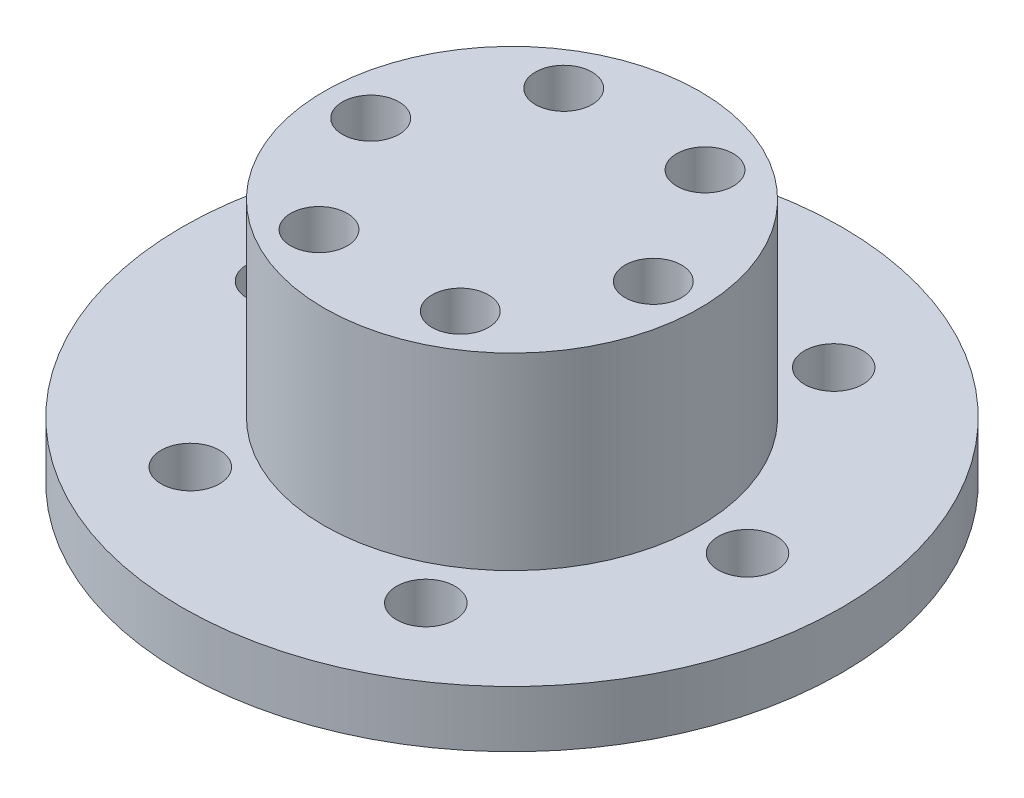
SolidWorks part; units mm, degrees
ref_plane "Alzado" through (0, 0, 0) normal (0, 0, 1) x (1, 0, 0)
ref_plane "Planta" through (0, 0, 0) normal (0, 1, 0) x (1, 0, 0)
ref_plane "Vista lateral" through (0, 0, 0) normal (1, 0, 0) x (0, 0, -1)
sketch "Croquis1" plane through (0, 0, 0) normal (0, 1, 0) x (1, 0, 0)
  circle A0 centre (0, 0) radius 12.5 construction
  circle A1 centre (12.5, 0) radius 1.55
  circle A2 centre (6.25, -10.8253) radius 1.55
  circle A3 centre (-6.25, -10.8253) radius 1.55
  circle A4 centre (-12.5, 0) radius 1.55
  circle A5 centre (-6.25, 10.8253) radius 1.55
  circle A6 centre (6.25, 10.8253) radius 1.55
  circle A7 centre (0, 0) radius 17.5
  point P17 (0, 0)
  dimension "D1" = 25
  dimension "D2" = 3.1
  dimension "D4" = 35
  dimension "D3" = 6
extrude "Saliente-Extruir1" add sketch "Croquis1" along normal blind 3
sketch "Croquis2" plane through (0, 3, 0) normal (0, 1, 0) x (1, 0, 0)
  circle A0 centre (0, 0) radius 9.97
  circle A1 centre (0, 0) radius 7.5 construction
  circle A2 centre (7.5, 0) radius 1.5
  circle A3 centre (3.75, -6.4952) radius 1.5
  circle A4 centre (-3.75, -6.4952) radius 1.5
  circle A5 centre (-7.5, 0) radius 1.5
  circle A6 centre (-3.75, 6.4952) radius 1.5
  circle A7 centre (3.75, 6.4952) radius 1.5
  point P18 (0, 0)
  dimension "D1" = 19.94
  dimension "D2" = 15
  dimension "D3" = 3
  dimension "D4" = 6
extrude "Saliente-Extruir2" add sketch "Croquis2" along normal blind 10
